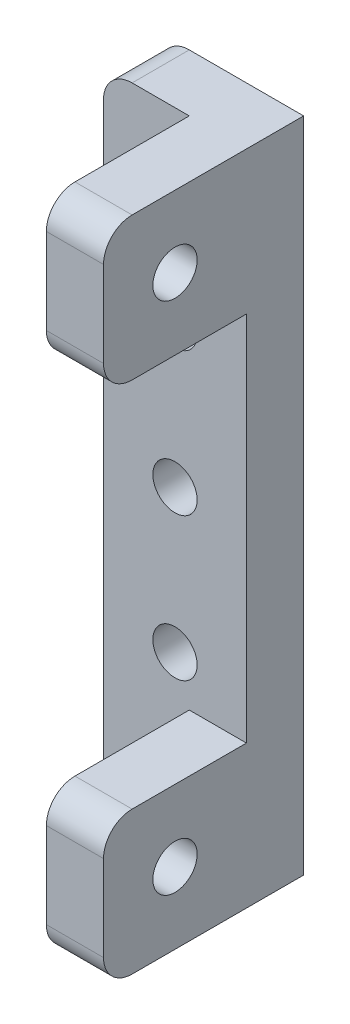
SolidWorks part; units mm, degrees
ref_plane "Front" through (0, 0, 0) normal (0, 0, 1) x (1, 0, 0)
ref_plane "Top" through (0, 0, 0) normal (0, 1, 0) x (1, 0, 0)
ref_plane "Right" through (0, 0, 0) normal (1, 0, 0) x (0, 0, -1)
sketch "Sketch1" plane through (0, 0, 0) normal (0, 0, 1) x (1, 0, 0)
  line L1 (-5, -23) -> (5, -23)
  line L2 (-5, -23) -> (-5, 23)
  line L3 (-5, 23) -> (5, 23)
  line L4 (5, -23) -> (5, 23)
  line L5 (-5, -23) -> (5, 23) construction
  line L6 (-5, 23) -> (5, -23) construction
  circle A0 centre (0, 10) radius 1.55
  circle A1 centre (0, 0) radius 1.55
  circle A2 centre (0, -10) radius 1.55
  point P0 (0, 0)
  point P12 (0, 0)
  dimension "D3" = 3.1
  dimension "D4" = 3.1
  dimension "D5" = 3.1
  dimension "D6" = 10
  dimension "D7" = 10
  dimension "D1" = 46
  dimension "D2" = 10
extrude "Boss-Extrude1" add sketch "Sketch1" along normal blind 4
sketch "Sketch2" plane through (0, 0, 4) normal (0, 0, 1) x (1, 0, 0)
  line L1 (5, 23) -> (1, 23)
  line L2 (5, 23) -> (5, 13)
  line L3 (5, 13) -> (1, 13)
  line L4 (1, 23) -> (1, 13)
  line L5 (5, 23) -> (1, 13) construction
  line L6 (5, 13) -> (1, 23) construction
  line L7 (5, -23) -> (1, -23)
  line L8 (5, -23) -> (5, -13)
  line L9 (5, -13) -> (1, -13)
  line L10 (1, -23) -> (1, -13)
  line L11 (5, -23) -> (1, -13) construction
  line L12 (5, -13) -> (1, -23) construction
  point P4 (3, 18)
  point P12 (3, -18)
  dimension "D3" = 10
  dimension "D1" = 4
  dimension "D2" = 10
extrude "Boss-Extrude2" add sketch "Sketch2" along normal blind 10
sketch "Sketch3" plane through (1, 0, 0) normal (-1, 0, 0) x (0, 0, 1)
  line L0 (14, 23) -> (4, 23) construction
  line L1 (14, 23) -> (14, 13) construction
  line L2 (14, -23) -> (4, -23) construction
  circle A0 centre (9, 18) radius 1.55
  circle A1 centre (9, -18) radius 1.55
  point P6 (0, 0)
  point P8 (0, 0)
  point P14 (0, 0)
  dimension "D1" = 3.1
  dimension "D2" = 3.1
  dimension "D3" = 5
  dimension "D4" = 5
  dimension "D5" = 5
extrude "Cut-Extrude1" cut sketch "Sketch3" against normal up to next
fillet "Fillet1" radius 2 6 edges at (3, 23, 14) (-5, 23, 2) (3, 13, 14) (-5, -23, 2) (3, -13, 14) (3, -23, 14)
